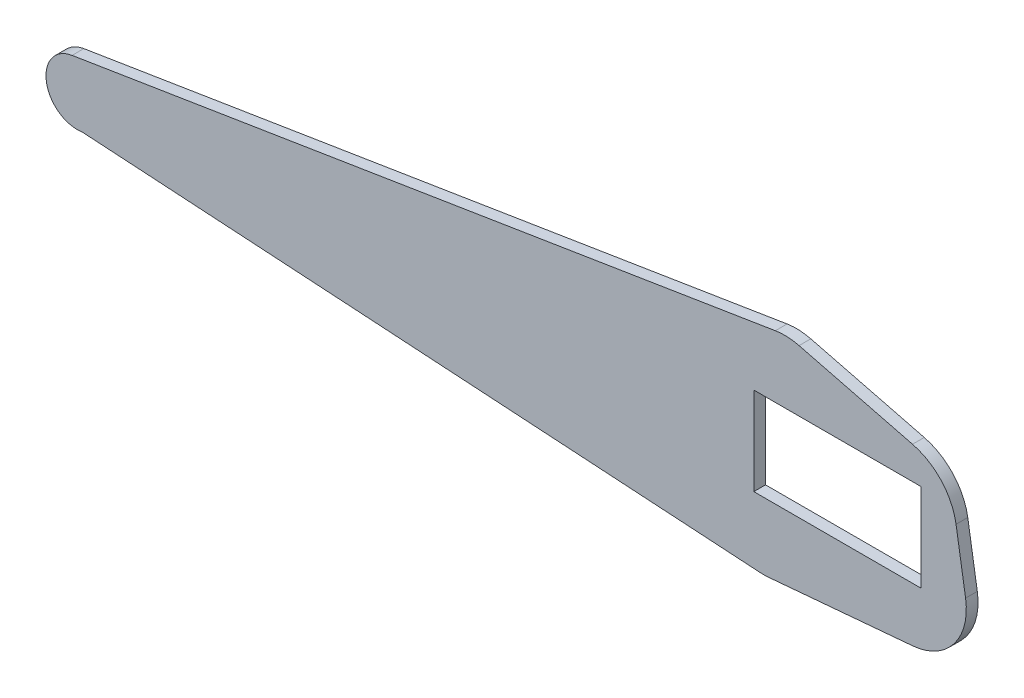
SolidWorks part; units mm, degrees
ref_plane "Plano frontal" through (0, 0, 0) normal (0, 0, 1) x (1, 0, 0)
ref_plane "Plano superior" through (0, 0, 0) normal (0, 1, 0) x (1, 0, 0)
ref_plane "Plano direito" through (0, 0, 0) normal (1, 0, 0) x (0, 0, -1)
sketch "Esboço1" plane through (0, 0, 0) normal (0, 0, 1) x (1, 0, 0)
  line L0 (11.4, 0) -> (5.3, 0) construction
  line L1 (11.4, 6) -> (-11.4, 6)
  line L2 (11.4, 6) -> (11.4, -6)
  line L3 (11.4, -6) -> (-11.4, -6)
  line L4 (-11.4, 6) -> (-11.4, -6)
  line L5 (11.4, 6) -> (-11.4, -6) construction
  line L6 (11.4, -6) -> (-11.4, 6) construction
  line L7 (5.3, 0) -> (-107.846, -6) construction
  line L8 (-107.846, -6) -> (-11.4, -6) construction
  line L10 (-104.3711, -0.9594) -> (-8.4592, 14.4747)
  line L11 (-5.2274, 14.3323) -> (10.2442, 10.4209)
  line L12 (16.1818, 3.9359) -> (17.4815, -4.1406)
  line L13 (10.2844, -13.3808) -> (-9.3426, -15.1081)
  line L14 (-10.5446, -15.1233) -> (-103.0251, -9.3235)
  arc A0 (-104.3711, -0.9594) -> (-103.0251, -9.3235) centre (-103.6981, -5.1414) ccw
  arc A1 (-9.3426, -15.1081) -> (-10.5446, -15.1233) centre (-10.0439, -7.139) cw
  arc A2 (10.2844, -13.3808) -> (17.4815, -4.1406) centre (9.5831, -5.4116) ccw
  arc A3 (16.1818, 3.9359) -> (10.2442, 10.4209) centre (8.2834, 2.6649) ccw
  arc A4 (-5.2274, 14.3323) -> (-8.4592, 14.4747) centre (-7.1882, 6.5763) ccw
  point P0 (0, 0)
  dimension "D5" = 8
  dimension "D1" = 12
  dimension "D2" = 22.8
  dimension "D3" = 6.1
  dimension "D4" = 113.305
  dimension "D6" = 97.1457
  dimension "D7" = 92.6622
extrude "Ressalto-extrusão1" add sketch "Esboço1" along normal blind 1.6
